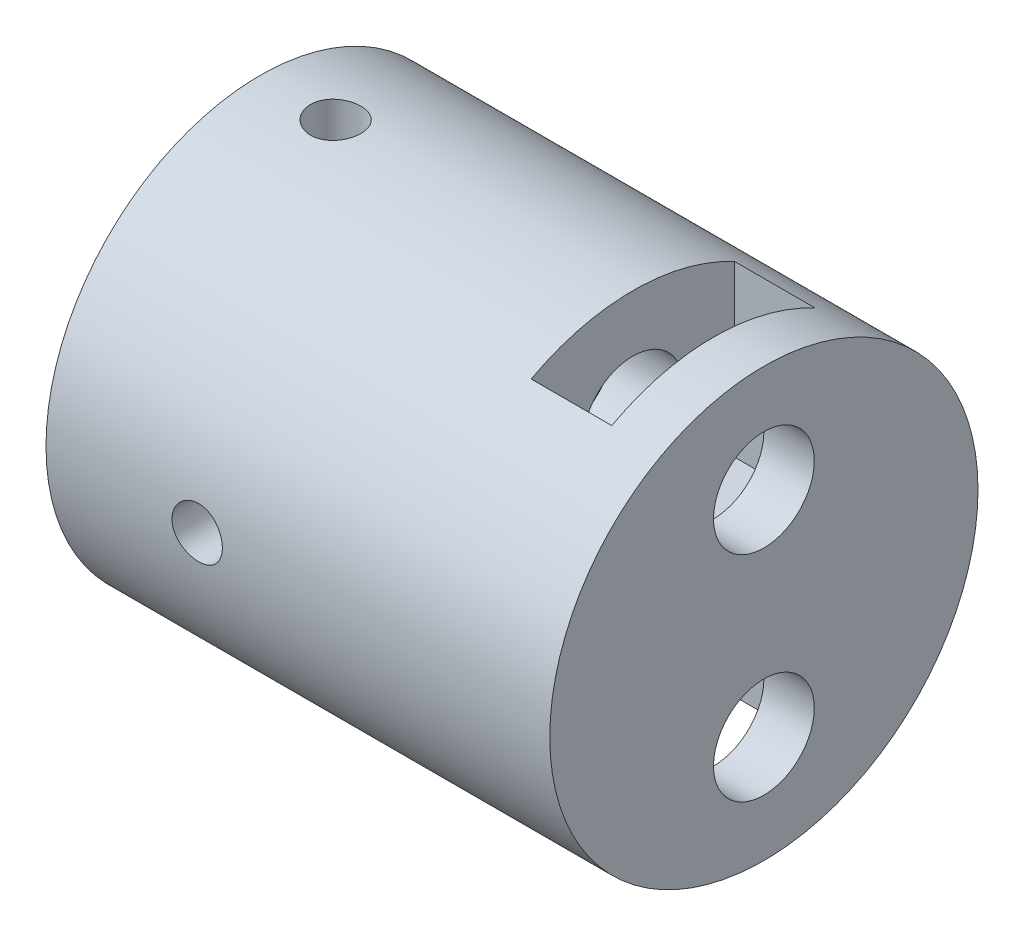
SolidWorks part; units mm, degrees
ref_plane "前视基准面" through (0, 0, 0) normal (0, 0, 1) x (1, 0, 0)
ref_plane "上视基准面" through (0, 0, 0) normal (0, 1, 0) x (1, 0, 0)
ref_plane "右视基准面" through (0, 0, 0) normal (1, 0, 0) x (0, 0, -1)
other "Configuration Table"
sketch "草图1" plane through (0, 0, 0) normal (1, 0, 0) x (0, 0, -1)
  circle A0 centre (0, 0) radius 8.5
  dimension "D1" = 17
extrude "凸台-拉伸1" add sketch "草图1" along normal blind 20
sketch "草图2" plane through (0, 0, 0) normal (-1, 0, 0) x (0, 0, 1)
  circle A0 centre (0, 0) radius 3.2
  dimension "D1" = 6.4
extrude "切除-拉伸1" cut sketch "草图2" against normal blind 9
sketch "草图3" plane through (0, 0, 0) normal (0, 1, 0) x (1, 0, 0)
  line L0 (0, 8.5) -> (0, -8.5) construction
  circle A0 centre (3, 0) radius 1
  dimension "D1" = 2
  dimension "D2" = 3
extrude "切除-拉伸2" cut sketch "草图3" against normal up to next and the other way up to next
sketch "草图4" plane through (0, 0, 0) normal (0, 0, 1) x (1, 0, 0)
  line L1 (0, 8.5) -> (0, -8.5) construction
  circle A0 centre (6, 0) radius 1
  dimension "D2" = 2
  dimension "D1" = 6
extrude "切除-拉伸3" cut sketch "草图4" against normal blind 19 and the other way blind 21
sketch "草图5" plane through (20, 0, 0) normal (1, 0, 0) x (0, 0, -1)
  line L0 (0, 0) -> (0, 8.5) construction
  circle A1 centre (0, 0) radius 8.5 construction
  circle A2 centre (0, 4.25) radius 2
  circle A3 centre (0, -4.25) radius 2
  dimension "D1" = 4
  dimension "D2" = 4
  dimension "D3" = 4.25
  dimension "D4" = 8.5
extrude "切除-拉伸4" cut sketch "草图5" against normal blind 8
ref_plane "基准面1" through (18, 0, 0) normal (1, 0, 0) x (0, 0, -1)
sketch "草图8" plane through (18, 0, 0) normal (1, 0, 0) x (0, 0, -1)
  line L0 (0, -8.5) -> (0, 8.5) construction
  line L2 (-4.0415, 4.25) -> (-2.0207, 0.75)
  line L3 (-2.0207, 0.75) -> (2.0207, 0.75)
  line L4 (2.0207, 0.75) -> (4.0415, 4.25)
  line L5 (4.0415, 4.25) -> (2.0207, 7.75)
  line L6 (2.0207, 7.75) -> (-2.0207, 7.75)
  line L7 (-2.0207, 7.75) -> (-4.0415, 4.25)
  line L8 (4.0415, -4.25) -> (2.0207, -0.75)
  line L9 (2.0207, -0.75) -> (-2.0207, -0.75)
  line L10 (-2.0207, -0.75) -> (-4.0415, -4.25)
  line L11 (-4.0415, -4.25) -> (-2.0207, -7.75)
  line L12 (-2.0207, -7.75) -> (2.0207, -7.75)
  line L13 (2.0207, -7.75) -> (4.0415, -4.25)
  circle A0 centre (0, 0) radius 8.5 construction
  circle A1 centre (0, 4.25) radius 3.5 construction
  circle A2 centre (0, -4.25) radius 3.5 construction
  dimension "D1" = 7
  dimension "D2" = 7
extrude "切除-拉伸6" cut sketch "草图8" against normal blind 3.2
ref_plane "基准面2" through (0, 8.5, 0) normal (0, 1, 0) x (1, 0, 0)
sketch "草图10" plane through (0, 8.5, 0) normal (0, 1, 0) x (1, 0, 0)
  line L0 (20, 0) -> (10.9704, 0) construction
  line L1 (20, -8.5) -> (20, 8.5) construction
  line L2 (18, -9.35) -> (18, 9.35) construction
  line L3 (18, 4.04) -> (14.8, 4.04)
  line L4 (18, 4.04) -> (18, -4.04)
  line L5 (18, -4.04) -> (14.8, -4.04)
  line L6 (14.8, 4.04) -> (14.8, -4.04)
  dimension "D1" = 3.2
  dimension "D2" = 8.08
  dimension "D3" = 4.04
extrude "切除-拉伸8" cut sketch "草图10" against normal offset from surface (7.75 mm away) 0.75 up to plane "上视基准面"
mirror "镜向1" about plane through (0, 0, 0) normal (0, 1, 0) of "切除-拉伸8"
